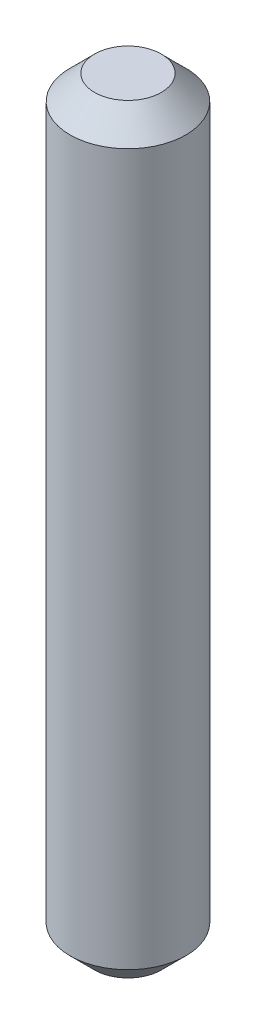
SolidWorks part; units mm, degrees
ref_plane "Front Plane" through (0, 0, 0) normal (0, 0, 1) x (1, 0, 0)
ref_plane "Top Plane" through (0, 0, 0) normal (0, 1, 0) x (1, 0, 0)
ref_plane "Right Plane" through (0, 0, 0) normal (1, 0, 0) x (0, 0, -1)
sketch "Sketch2" plane through (0, 0, 0) normal (0, 1, 0) x (1, 0, 0)
  circle A0 centre (0, 0) radius 2.9972
  dimension "D1" = 5.9944
extrude "Boss-Extrude1" add sketch "Sketch2" along normal blind 39.37
chamfer "Chamfer1" distance 1.27 angle 45 2 edges at (0, 39.37, 2.9972) (0, 0, 2.9972)
